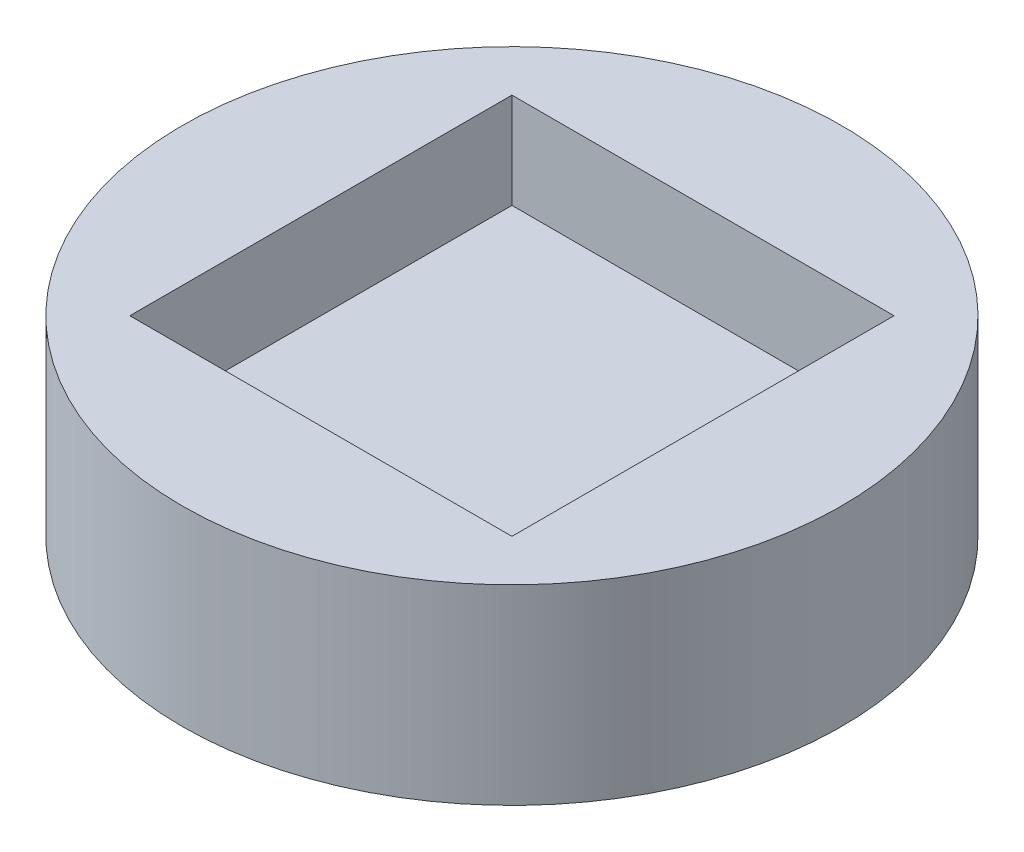
SolidWorks part; units mm, degrees
ref_plane "Front Plane" through (0, 0, 0) normal (0, 0, 1) x (1, 0, 0)
ref_plane "Top Plane" through (0, 0, 0) normal (0, 1, 0) x (1, 0, 0)
ref_plane "Right Plane" through (0, 0, 0) normal (1, 0, 0) x (0, 0, -1)
sketch "Sketch1" plane through (0, 0, 0) normal (0, 1, 0) x (1, 0, 0)
  circle A0 centre (0, 0) radius 3.45
  dimension "D1" = 6.9
extrude "Boss-Extrude1" add sketch "Sketch1" along normal blind 2
sketch "Sketch2" plane through (0, 2, 0) normal (0, 1, 0) x (1, 0, 0)
  line L1 (2, 2) -> (-2, 2)
  line L2 (2, 2) -> (2, -2)
  line L3 (2, -2) -> (-2, -2)
  line L4 (-2, 2) -> (-2, -2)
  line L5 (2, 2) -> (-2, -2) construction
  line L6 (2, -2) -> (-2, 2) construction
  point P0 (0, 0)
  dimension "D1" = 4
  dimension "D2" = 4
extrude "Cut-Extrude1" cut sketch "Sketch2" against normal blind 1
